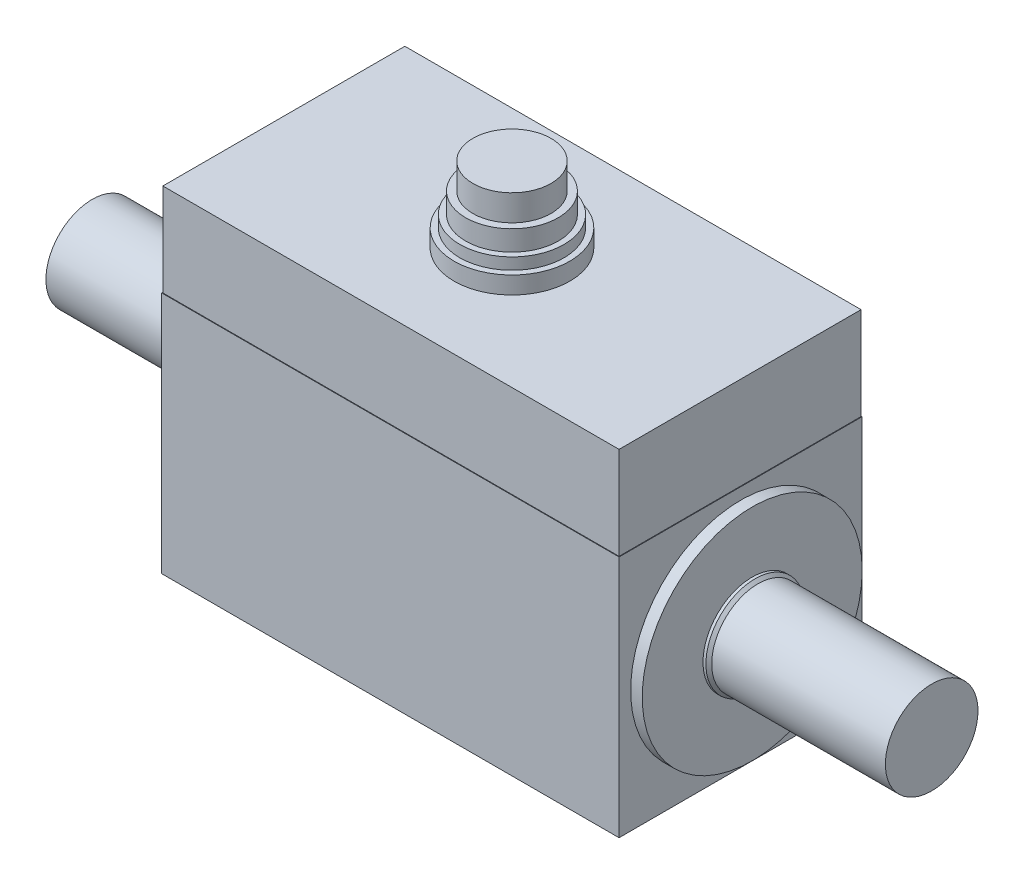
SolidWorks part; units mm, degrees
ref_plane "Front Plane" through (0, 0, 0) normal (0, 0, 1) x (1, 0, 0)
ref_plane "Top Plane" through (0, 0, 0) normal (0, 1, 0) x (1, 0, 0)
ref_plane "Right Plane" through (0, 0, 0) normal (1, 0, 0) x (0, 0, -1)
ref_plane "Plane1" through (0, 21, 0) normal (0, 1, 0) x (1, 0, 0)
sketch "Sketch1" plane through (0, 21, 0) normal (0, 1, 0) x (1, 0, 0)
  line L0 (-39.5, -21) -> (39.5, -21)
  line L1 (39.5, -21) -> (39.5, 21)
  line L2 (39.5, 21) -> (-39.5, 21)
  line L3 (-39.5, 21) -> (-39.5, -21)
extrude "Boss-Extrude1" add sketch "Sketch1" against normal blind 42
sketch "Sketch2" plane through (0, 21, 0) normal (0, 1, 0) x (-1, 0, 0)
  line L0 (-39.4, -20.9) -> (-39.4, 20.9)
  line L1 (-39.4, 20.9) -> (39.4, 20.9)
  line L2 (39.4, 20.9) -> (39.4, -20.9)
  line L3 (39.4, -20.9) -> (-39.4, -20.9)
extrude "Boss-Extrude2" add sketch "Sketch2" along normal blind 16
sketch "Sketch3" plane through (0, 0, -21) normal (0, 0, -1) x (-1, 0, 0)
  line L0 (29, 14) -> (29, -12)
  line L1 (29, -12) -> (-29, -12)
  line L2 (-29, -12) -> (-29, 14)
  line L3 (-29, 14) -> (29, 14)
extrude "Boss-Extrude3" add sketch "Sketch3" along normal blind 0.5
sketch "Sketch4" plane through (0, 0, -21.5) normal (0, 0, -1) x (-1, 0, 0)
  line L0 (19, -7) -> (19, 4)
  line L1 (19, 4) -> (-23, 4)
  line L2 (-23, 4) -> (-23, -7)
  line L3 (-23, -7) -> (19, -7)
extrude "Cut-Extrude1" cut sketch "Sketch4" against normal blind 0.25
ref_plane "Plane2" through (0, 0, 0) normal (0, 0, -1) x (-1, 0, 0)
sketch "Sketch5" plane through (0, 0, 0) normal (0, 0, -1) x (-1, 0, 0)
  line L0 (-10, 37) -> (0, 37)
  line L1 (0, 37) -> (0, 50)
  line L2 (0, 50) -> (-6.75, 50)
  line L3 (-6.75, 50) -> (-6.75, 45.5)
  line L4 (-6.75, 45.5) -> (-8, 45.5)
  line L5 (-8, 45.5) -> (-8, 42)
  line L6 (-8, 42) -> (-9, 42)
  line L7 (-9, 42) -> (-9, 40)
  line L8 (-9, 40) -> (-10, 40)
  line L9 (-10, 40) -> (-10, 37)
  line L10 (0, 37) -> (0, 50) construction
revolve "Revolve1" add sketch "Sketch5" angle 360 about L10
sketch "Sketch6" plane through (0, 0, 0) normal (0, 0, 1) x (1, 0, 0)
  line L0 (39.5, 19) -> (39.5, 0)
  line L1 (39.5, 0) -> (72.5, 0)
  line L2 (72.5, 0) -> (72.5, 8)
  line L3 (72.5, 8) -> (42.5, 8)
  line L4 (42.5, 8) -> (42, 8.5)
  line L5 (42, 8.5) -> (41.5, 8.5)
  line L6 (41.5, 8.5) -> (41.5, 19)
  line L7 (41.5, 19) -> (39.5, 19)
  line L8 (39.5, 0) -> (72.5, 0) construction
revolve "Revolve2" add sketch "Sketch6" angle 360 about L8
sketch "Sketch7" plane through (0, 0, 0) normal (0, 0, 1) x (1, 0, 0)
  line L0 (-72.5, 8) -> (-72.5, 0)
  line L1 (-72.5, 0) -> (-39.5, 0)
  line L2 (-39.5, 0) -> (-39.5, 19)
  line L3 (-39.5, 19) -> (-41.5, 19)
  line L4 (-41.5, 19) -> (-41.5, 8.5)
  line L5 (-41.5, 8.5) -> (-42, 8.5)
  line L6 (-42, 8.5) -> (-42.5, 8)
  line L7 (-42.5, 8) -> (-72.5, 8)
  line L8 (-72.5, 0) -> (-39.5, 0) construction
revolve "Revolve3" add sketch "Sketch7" angle 360 about L8
hole_wizard "M2 Clearance Hole1" positions "Sketch11" profile "Sketch10" hole size "M2" standard "ANSI Metric"
sketch "Sketch11" plane through (-39.5, 0, 0) normal (-1, 0, 0) x (0, 0, 1)
  point P0 (-16.2635, 16.2635)
  point P1 (16.2635, 16.2635)
  point P2 (16.2635, -16.2635)
  point P3 (-16.2635, -16.2635)
sketch "Sketch10" plane through (-39.5, 16.2635, -16.2635) normal (0, 1, 0) x (0, 0, 1)
  line L0 (0, 0) -> (0, 7.6099)
  line L1 (0, 7.6099) -> (1.2295, 6.9)
  line L2 (1.2295, 6.9) -> (1.2295, 0)
  line L5 (1.2295, 0) -> (0, 0)
  line L10 (0, 7.6099) -> (-1.2295, 6.9) construction
  line L11 (0, -6.35) -> (0, 107.95) construction
  dimension "Hole Dia." = 2.459
  dimension "Hole Depth" = 6.9
  dimension "Drill Angle" = 120
hole_wizard "M2 Clearance Hole2" positions "Sketch13" profile "Sketch12" hole size "M2" standard "ANSI Metric"
sketch "Sketch13" plane through (0, -21, 0) normal (0, -1, 0) x (1, 0, 0)
  point P0 (30, 16)
  point P1 (-30, 16)
  point P2 (30, -16)
  point P3 (-30, -16)
sketch "Sketch12" plane through (30, -21, 16) normal (1, 0, 0) x (0, 0, -1)
  line L0 (0, 0) -> (0, 7.9099)
  line L1 (0, 7.9099) -> (1.2295, 7.2)
  line L2 (1.2295, 7.2) -> (1.2295, 0)
  line L5 (1.2295, 0) -> (0, 0)
  line L10 (0, 7.9099) -> (-1.2295, 7.2) construction
  line L11 (0, -6.35) -> (0, 107.95) construction
  dimension "Hole Dia." = 2.459
  dimension "Hole Depth" = 7.2
  dimension "Drill Angle" = 120
chamfer "Chamfer1" distance 0.2705 angle 45 8 edges at (30, -21, -17.2295) (30, -21, 14.7705) (-39.5, 16.2635, -15.034) (-39.5, -16.2635, -15.034) (-30, -21, 14.7705) (-30, -21, -17.2295) (-39.5, -16.2635, 17.493) (-39.5, 16.2635, 17.493)
